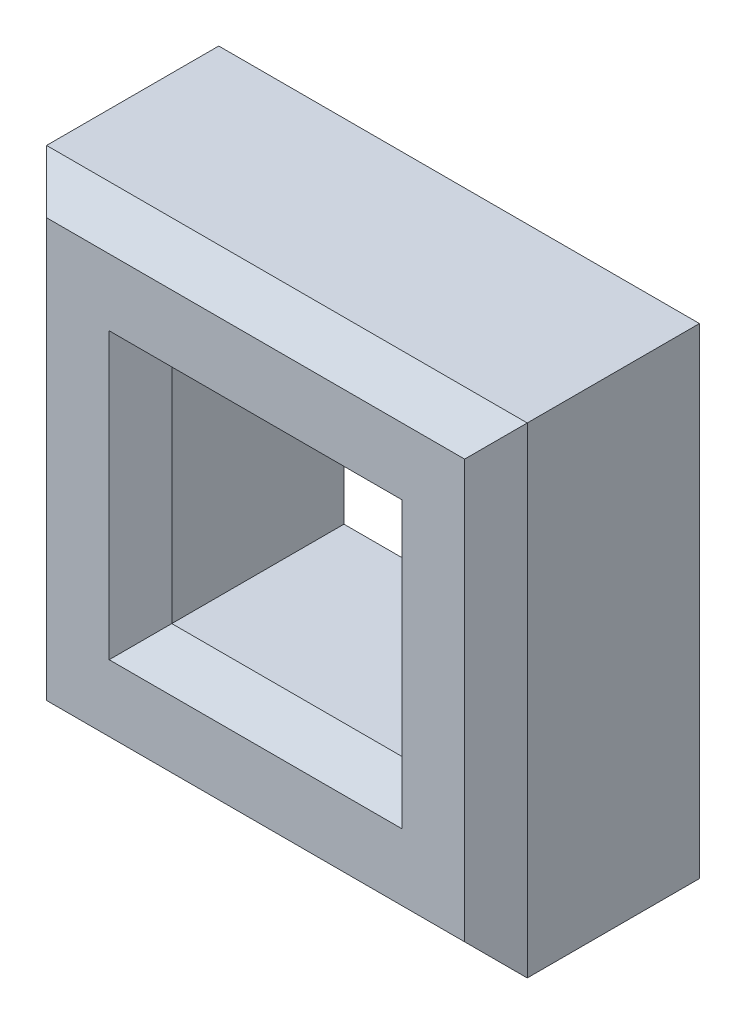
SolidWorks part; units mm, degrees
ref_plane "Front Plane" through (0, 0, 0) normal (0, 0, 1) x (1, 0, 0)
ref_plane "Top Plane" through (0, 0, 0) normal (0, 1, 0) x (1, 0, 0)
ref_plane "Right Plane" through (0, 0, 0) normal (1, 0, 0) x (0, 0, -1)
sketch "Sketch1" plane through (0, 0, 0) normal (0, 0, 1) x (1, 0, 0)
  line L1 (3.677, -3.55) -> (-3.677, -3.55)
  line L2 (3.677, -3.55) -> (3.677, 3.55)
  line L3 (3.677, 3.55) -> (-3.677, 3.55)
  line L4 (-3.677, -3.55) -> (-3.677, 3.55)
  line L7 (7.677, -7.677) -> (-7.677, -7.677)
  line L8 (7.677, -7.677) -> (7.677, 7.677)
  line L9 (7.677, 7.677) -> (-7.677, 7.677)
  line L10 (-7.677, -7.677) -> (-7.677, 7.677)
  point P0 (0, 0)
  point P2 (0, 3.55)
  point P7 (0, 0)
  point P12 (0, 7.677)
  point P13 (0, 0)
  point P14 (-3.677, 0)
  point P15 (-7.677, 0)
  dimension "D2" = 7.3539
  dimension "D1" = 4
  dimension "D3" = 7.1
extrude "Boss-Extrude1" add sketch "Sketch1" along normal blind 6.5
chamfer "Chamfer1" distance 1 angle 45 8 edges at (3.677, 0, 6.5) (0, 3.55, 6.5) (-3.677, 0, 6.5) (0, -3.55, 6.5) (0, 7.677, 6.5) (7.677, 0, 6.5) (0, -7.677, 6.5) (-7.677, 0, 6.5)
